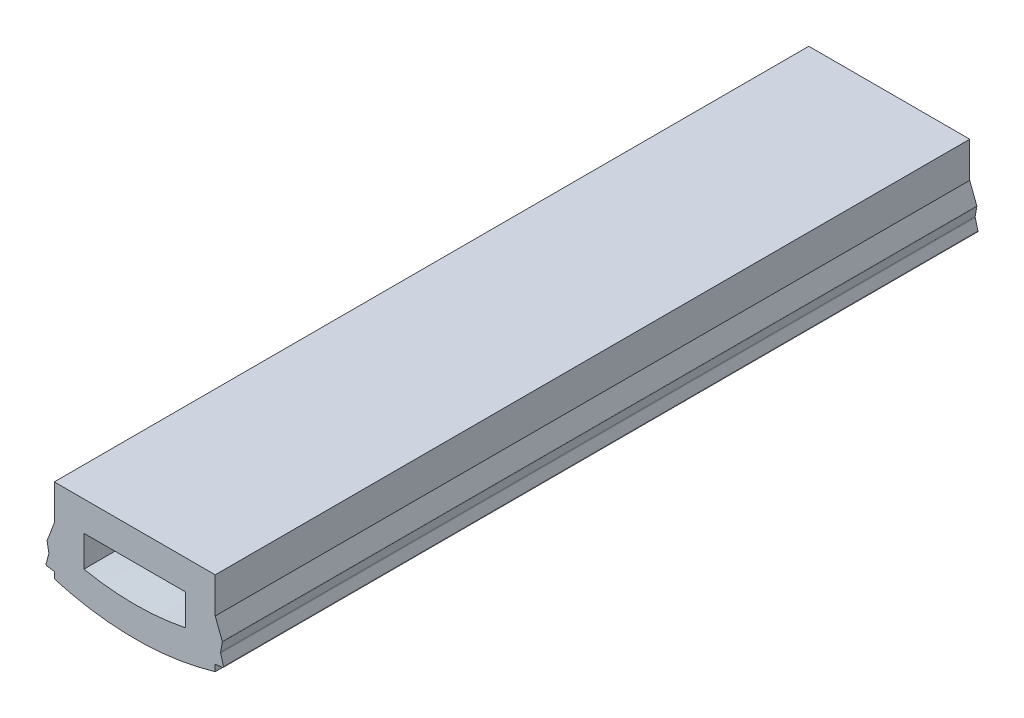
SolidWorks part; units mm, degrees
ref_plane "Ön Düzlem" through (0, 0, 0) normal (0, 0, 1) x (1, 0, 0)
ref_plane "Üst Düzlem" through (0, 0, 0) normal (0, 1, 0) x (1, 0, 0)
ref_plane "Sağ Düzlem" through (0, 0, 0) normal (1, 0, 0) x (0, 0, -1)
sketch "Sketch1" plane through (0, 0, 0) normal (0, 0, 1) x (1, 0, 0)
  line L11 (-15.9577, -92.1739) -> (-15.9577, -75.4867)
  line L12 (16.0423, -75.4867) -> (-15.9577, -75.4867)
  line L14 (16.0423, -75.4867) -> (16.0423, -92.1739)
  line L15 (-10.1, -87.5818) -> (-10.1, -81.4)
  line L16 (10.1, -81.4) -> (-10.1, -81.4)
  line L17 (10.1, -81.4) -> (10.1, -87.5818)
  arc A73 (10.1, -87.5818) -> (-10.1, -87.5818) centre (0, -38) cw
  arc A101 (16.0423, -92.1739) -> (-15.9577, -92.1739) centre (0.0423, -37.9867) cw
  point P0 (0, 0)
  point P1 (0, 0)
extrude "Boss-Extrude2" add sketch "Sketch1" against normal blind 150
sketch "Sketch4" plane through (0, 0, 0) normal (0, 0, 1) x (1, 0, 0)
  line L3 (16.0423, -92.1739) -> (16.0423, -75.4867)
  line L4 (16.0423, -75.4867) -> (-15.9577, -75.4867)
  line L5 (-15.9577, -75.4867) -> (-15.9577, -92.1739)
  line L6 (16.0423, -92.1739) -> (16.0423, -75.4867)
  line L7 (16.0423, -75.4867) -> (-15.9577, -75.4867)
  line L8 (-15.9577, -75.4867) -> (-15.9577, -92.1739)
  line L9 (10.1423, -87.5685) -> (10.1423, -81.3867)
  line L10 (10.1423, -81.3867) -> (-10.0577, -81.3867)
  line L11 (-10.0577, -81.3867) -> (-10.0577, -87.5685)
  arc A1 (-15.9577, -92.1739) -> (16.0423, -92.1739) centre (0.0423, -37.9867) ccw
  arc A2 (-15.9577, -92.1739) -> (16.0423, -92.1739) centre (0.0423, -37.9867) ccw
  arc A3 (-10.0577, -87.5685) -> (10.1423, -87.5685) centre (0.0423, -37.9867) ccw
  dimension "D1" = 0
extrude "Cut-Extrude1" cut sketch "Sketch4" against normal through all draft 0.75 draft outward yes
sketch "Sketch5" plane through (0, 0, -150) normal (0, 0, -1) x (-1, 0, 0)
  line L0 (15.9577, -90.8939) -> (15.9577, -82.5707)
  line L1 (17.592, -90.4507) -> (17.0492, -88.4247)
  line L2 (17.0416, -88.2521) -> (17.3733, -86.3597)
  line L3 (17.3632, -86.2538) -> (15.9577, -82.5707)
  line L4 (15.9577, -90.8939) -> (17.425, -90.7007)
  line L5 (15.9577, -92.1739) -> (15.9577, -90.8939)
  line L6 (15.9577, -92.1739) -> (15.9577, -75.4867) construction
  line L8 (-0.0423, -1094.4867) -> (-0.0423, 48905.5133) construction
  line L9 (-16.0423, -90.8939) -> (-17.5096, -90.7007)
  line L10 (-17.6767, -90.4507) -> (-17.1338, -88.4247)
  line L11 (-17.1262, -88.2521) -> (-17.458, -86.3597)
  line L12 (-17.4478, -86.2538) -> (-16.0423, -82.5707)
  line L13 (-16.0423, -90.8939) -> (-16.0423, -82.5707)
  arc A0 (17.425, -90.7007) -> (17.592, -90.4507) centre (17.3989, -90.5024) ccw
  arc A1 (17.0416, -88.2521) -> (17.0492, -88.4247) centre (17.4355, -88.3211) ccw
  arc A2 (17.3733, -86.3597) -> (17.3632, -86.2538) centre (17.1763, -86.3252) ccw
  arc A3 (-16.0423, -92.1739) -> (15.9577, -92.1739) centre (-0.0423, -37.9867) ccw construction
  arc A4 (-17.5096, -90.7007) -> (-17.6767, -90.4507) centre (-17.4835, -90.5024) cw
  arc A5 (-17.1262, -88.2521) -> (-17.1338, -88.4247) centre (-17.5202, -88.3211) cw
  arc A6 (-17.458, -86.3597) -> (-17.4478, -86.2538) centre (-17.261, -86.3252) cw
  point P11 (15.9577, -92.1739)
  point P25 (-0.0423, -94.4867)
  line M25 (-16.0423, -75.4867) -> (-16.0423, -92.1739)
extrude "Boss-Extrude3" add sketch "Sketch5" against normal up to surface (150 mm away) contours A6 L11 A5 L10 A4 L9 L12 M25 | L0 L3 A2 L2 A1 L1 A0 L4 up to face at (0.0423, -84.7322, 0)
